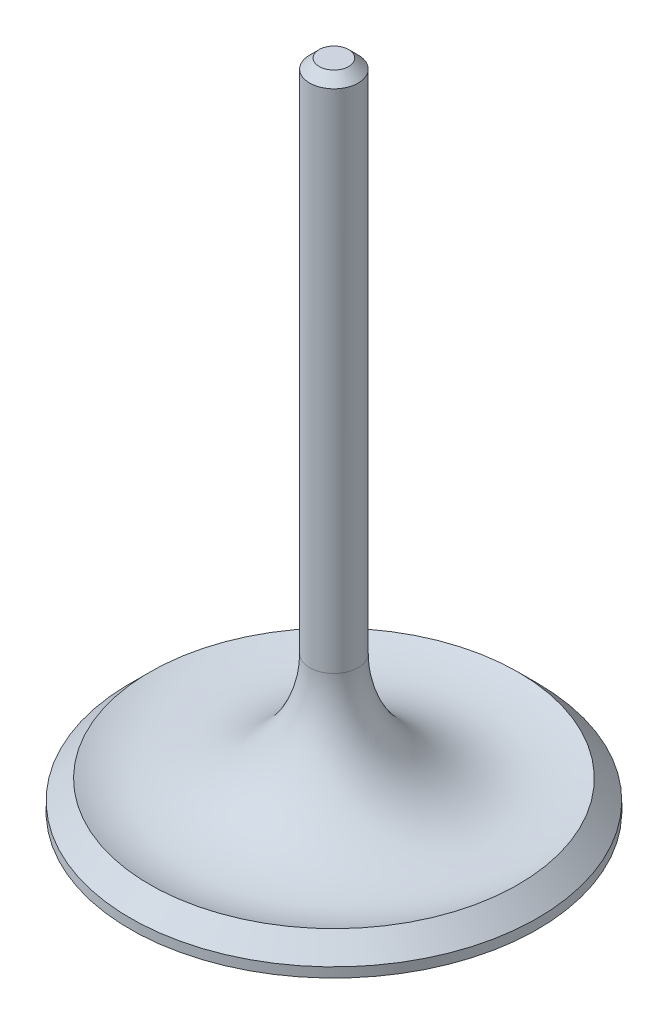
SolidWorks part; units mm, degrees
ref_plane "Front Plane" through (0, 0, 0) normal (0, 0, 1) x (1, 0, 0)
ref_plane "Top Plane" through (0, 0, 0) normal (0, 1, 0) x (1, 0, 0)
ref_plane "Right Plane" through (0, 0, 0) normal (1, 0, 0) x (0, 0, -1)
sketch "Sketch1" plane through (0, 0, 0) normal (0, 0, 1) x (1, 0, 0)
  line L0 (0, 0) -> (0, 85.55)
  line L1 (0, 85.55) -> (3.18, 85.55)
  line L2 (3.18, 85.55) -> (3.18, 17.9547)
  line L4 (26.67, 1.27) -> (26.67, 0)
  line L5 (26.67, 0) -> (0, 0)
  line L6 (26.67, 1.27) -> (24.13, 3.81)
  arc A0 (3.18, 17.9547) -> (24.13, 3.81) centre (18.43, 17.9547) ccw
  dimension "D5" = 3.81
  dimension "D6" = 15.25
  dimension "D1" = 85.55
  dimension "D2" = 26.67
  dimension "D3" = 3.18
  dimension "D4" = 1.27
  dimension "D7" = 45
revolve "Revolve1" add sketch "Sketch1" angle 360 about L0
chamfer "Chamfer1" distance 1.25 angle 45 1 edges at (0, 85.55, -3.18)
